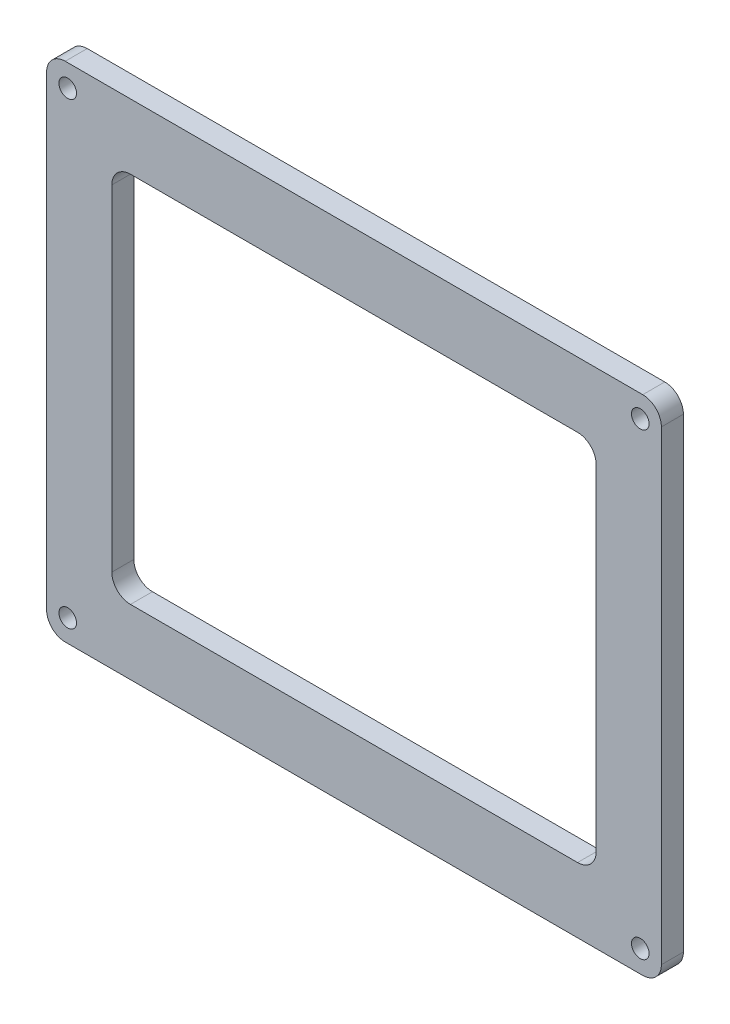
SolidWorks part; units mm, degrees
ref_plane "Front Plane" through (0, 0, 0) normal (0, 0, 1) x (1, 0, 0)
ref_plane "Top Plane" through (0, 0, 0) normal (0, 1, 0) x (1, 0, 0)
ref_plane "Right Plane" through (0, 0, 0) normal (1, 0, 0) x (0, 0, -1)
sketch "Sketch1" plane through (0, 0, 0) normal (0, 0, 1) x (1, 0, 0)
  line L1 (-30.48, 25.4) -> (30.48, 25.4)
  line L2 (-33.02, 22.86) -> (-33.02, -22.86)
  line L3 (-30.48, -25.4) -> (30.48, -25.4)
  line L4 (33.02, 22.86) -> (33.02, -22.86)
  line L5 (-33.02, 25.4) -> (33.02, -25.4) construction
  line L6 (-33.02, -25.4) -> (33.02, 25.4) construction
  line L7 (39.37, 34.29) -> (-39.37, 34.29)
  line L8 (41.91, 31.75) -> (41.91, -31.75)
  line L9 (39.37, -34.29) -> (-39.37, -34.29)
  line L10 (-41.91, 31.75) -> (-41.91, -31.75)
  line L11 (41.91, 34.29) -> (-41.91, -34.29) construction
  line L12 (41.91, -34.29) -> (-41.91, 34.29) construction
  arc A0 (30.48, 25.4) -> (33.02, 22.86) centre (30.48, 22.86) cw
  arc A1 (30.48, -25.4) -> (33.02, -22.86) centre (30.48, -22.86) ccw
  arc A2 (-33.02, -22.86) -> (-30.48, -25.4) centre (-30.48, -22.86) ccw
  arc A3 (-30.48, 25.4) -> (-33.02, 22.86) centre (-30.48, 22.86) ccw
  arc A4 (-39.37, -34.29) -> (-41.91, -31.75) centre (-39.37, -31.75) cw
  arc A5 (41.91, -31.75) -> (39.37, -34.29) centre (39.37, -31.75) cw
  arc A6 (39.37, 34.29) -> (41.91, 31.75) centre (39.37, 31.75) cw
  arc A7 (-39.37, 34.29) -> (-41.91, 31.75) centre (-39.37, 31.75) ccw
  point P0 (0, 0)
  point P18 (0, 0)
  dimension "D3" = 2.54
  dimension "D6" = 2.54
  dimension "D1" = 50.8
  dimension "D2" = 66.04
  dimension "D4" = 68.58
  dimension "D5" = 83.82
extrude "Boss-Extrude1" add sketch "Sketch1" along normal blind 3
sketch "Sketch2" plane through (0, 0, 3) normal (0, 0, 1) x (1, 0, 0)
  point P0 (-39.0331, 31.2671)
  point P1 (0, 0)
hole_wizard "M2 Clearance Hole1" positions "3DSketch1" profile "Sketch3" hole size "M2" standard "ANSI Metric"
sketch3d "3DSketch1"
  point P0 (-39.0331, 31.2671, 3)
sketch "Sketch3" plane through (-39.0331, 31.2671, 3) normal (1, 0, 0) x (0, -1, 0)
  line L0 (0, 0) -> (0, 3.769)
  line L1 (0, 3.769) -> (1.2, 3.048)
  line L2 (1.2, 3.048) -> (1.2, 0)
  line L5 (1.2, 0) -> (0, 0)
  line L10 (0, 3.769) -> (-1.2, 3.048) construction
  line L11 (0, -6.35) -> (0, 107.95) construction
  dimension "Hole Dia." = 2.4
  dimension "Hole Depth" = 3.048
  dimension "Drill Angle" = 118
mirror "Mirror1" about plane through (0, 0, 0) normal (0, 1, 0) of "M2 Clearance Hole1"
mirror "Mirror2" about plane through (0, 0, 0) normal (1, 0, 0) of "Mirror1", "M2 Clearance Hole1"
sketch "Sketch4" plane through (0, 0, 3) normal (0, 0, 1) x (1, 0, 0)
  circle A0 centre (-39.0331, -31.2671) radius 1.2 construction
  circle A1 centre (39.0331, -31.2671) radius 1.2 construction
  circle A2 centre (39.0331, 31.2671) radius 1.2 construction
  circle A3 centre (-39.0331, 31.2671) radius 1.2 construction
  circle A4 centre (-39.0331, -31.2671) radius 1.2
  circle A5 centre (39.0331, -31.2671) radius 1.2
  circle A6 centre (39.0331, 31.2671) radius 1.2
  circle A7 centre (-39.0331, 31.2671) radius 1.2
